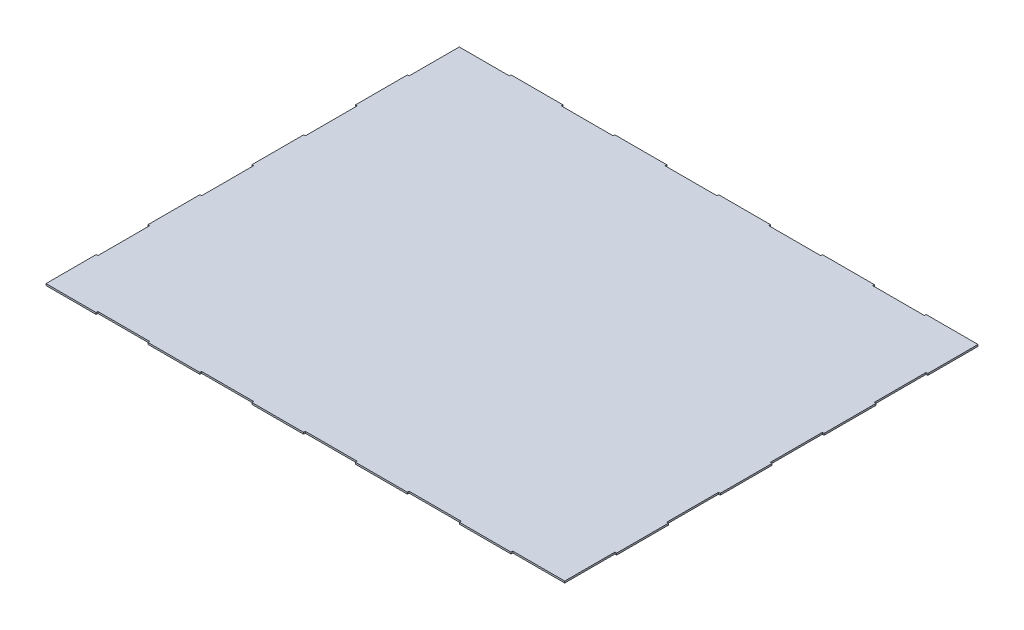
SolidWorks part; units mm, degrees
ref_plane "Front Plane" through (0, 0, 0) normal (0, 0, 1) x (1, 0, 0)
ref_plane "Top Plane" through (0, 0, 0) normal (0, 1, 0) x (1, 0, 0)
ref_plane "Right Plane" through (0, 0, 0) normal (1, 0, 0) x (0, 0, -1)
sketch "Sketch1" plane through (0, 0, 0) normal (0, 1, 0) x (1, 0, 0)
  line L0 (0, 0) -> (58, 0)
  line L1 (58, 0) -> (58, 2)
  line L2 (58, 2) -> (118, 2)
  line L3 (118, 2) -> (118, 0)
  line L4 (118, 0) -> (178, 0)
  line L5 (178, 0) -> (178, 2)
  line L6 (178, 2) -> (238, 2)
  line L7 (238, 2) -> (238, 0)
  line L8 (238, 0) -> (298, 0)
  line L9 (298, 0) -> (298, 2)
  line L10 (298, 2) -> (358, 2)
  line L11 (358, 2) -> (358, 0)
  line L12 (358, 0) -> (418, 0)
  line L13 (418, 0) -> (418, 2)
  line L14 (418, 2) -> (478, 2)
  line L15 (478, 2) -> (478, 0)
  line L16 (478, 0) -> (538, 0)
  line L17 (538, 0) -> (538, 2)
  line L18 (538, 2) -> (598, 2)
  line L19 (0, 0) -> (0, 58)
  line L20 (0, 58) -> (2, 58)
  line L21 (2, 58) -> (2, 118)
  line L22 (2, 118) -> (0, 118)
  line L23 (0, 118) -> (0, 178)
  line L24 (0, 178) -> (2, 178)
  line L25 (2, 178) -> (2, 238)
  line L26 (2, 238) -> (0, 238)
  line L27 (0, 238) -> (0, 298)
  line L28 (0, 298) -> (2, 298)
  line L29 (2, 298) -> (2, 358)
  line L30 (2, 358) -> (0, 358)
  line L31 (0, 358) -> (0, 418)
  line L32 (0, 418) -> (2, 418)
  line L33 (2, 418) -> (2, 476)
  line L34 (60, 476) -> (2, 476)
  line L35 (60, 476) -> (60, 478)
  line L36 (60, 478) -> (120, 478)
  line L37 (120, 478) -> (120, 476)
  line L38 (120, 476) -> (180, 476)
  line L39 (180, 476) -> (180, 478)
  line L40 (180, 478) -> (240, 478)
  line L41 (240, 478) -> (240, 476)
  line L42 (240, 476) -> (300, 476)
  line L43 (300, 476) -> (300, 478)
  line L44 (300, 478) -> (360, 478)
  line L45 (360, 478) -> (360, 476)
  line L46 (360, 476) -> (420, 476)
  line L47 (420, 476) -> (420, 478)
  line L48 (420, 478) -> (480, 478)
  line L49 (480, 478) -> (480, 476)
  line L50 (480, 476) -> (540, 476)
  line L51 (540, 476) -> (540, 478)
  line L52 (540, 478) -> (600, 478)
  line L53 (600, 478) -> (600, 420)
  line L54 (600, 420) -> (598, 420)
  line L55 (598, 420) -> (598, 360)
  line L56 (598, 360) -> (600, 360)
  line L57 (600, 360) -> (600, 300)
  line L58 (600, 300) -> (598, 300)
  line L59 (598, 300) -> (598, 240)
  line L60 (598, 240) -> (600, 240)
  line L61 (600, 240) -> (600, 180)
  line L62 (600, 180) -> (598, 180)
  line L63 (598, 180) -> (598, 120)
  line L64 (598, 120) -> (600, 120)
  line L65 (600, 120) -> (600, 60)
  line L66 (600, 60) -> (598, 60)
  line L67 (598, 60) -> (598, 2)
  point P3 (598, 181.7228)
  point P22 (598, 133.4645)
  point P71 (510, 476)
  point P72 (598, 116.4486)
  point P73 (598, 84.6483)
  point P74 (598, 60.3796)
  dimension "D2" = 2
  dimension "D6" = 58
  dimension "D7" = 60
  dimension "D8" = 2
  dimension "D9" = 60
  dimension "D10" = 2
  dimension "D11" = 2
  dimension "D12" = 2
  dimension "D13" = 2
  dimension "D14" = 2
  dimension "D15" = 2
  dimension "D16" = 60
  dimension "D17" = 2
  dimension "D18" = 60
  dimension "D19" = 60
  dimension "D20" = 2
  dimension "D21" = 60
  dimension "D22" = 60
  dimension "D23" = 60
  dimension "D24" = 60
  dimension "D25" = 58
  dimension "D26" = 60
  dimension "D27" = 60
  dimension "D28" = 60
  dimension "D29" = 60
  dimension "D30" = 60
  dimension "D31" = 60
  dimension "D32" = 60
  dimension "D33" = 60
  dimension "D34" = 60
  dimension "D35" = 58
  dimension "D36" = 2
  dimension "D37" = 2
  dimension "D38" = 2
  dimension "D39" = 2
  dimension "D40" = 60
  dimension "D41" = 60
  dimension "D42" = 60
  dimension "D43" = 60
  dimension "D44" = 60
  dimension "D45" = 60
  dimension "D46" = 58
  dimension "D47" = 2
  dimension "D48" = 2
  dimension "D49" = 2
  dimension "D50" = 2
  dimension "D51" = 2
  dimension "D52" = 2
  dimension "D53" = 2
  dimension "D54" = 2
  dimension "D55" = 2
  dimension "D56" = 2
  dimension "D57" = 2
  dimension "D58" = 60
  dimension "D59" = 60
  dimension "D60" = 60
  dimension "D61" = 60
  dimension "D62" = 60
  dimension "D63" = 60
extrude "Boss-Extrude1" add sketch "Sketch1" along normal blind 2
